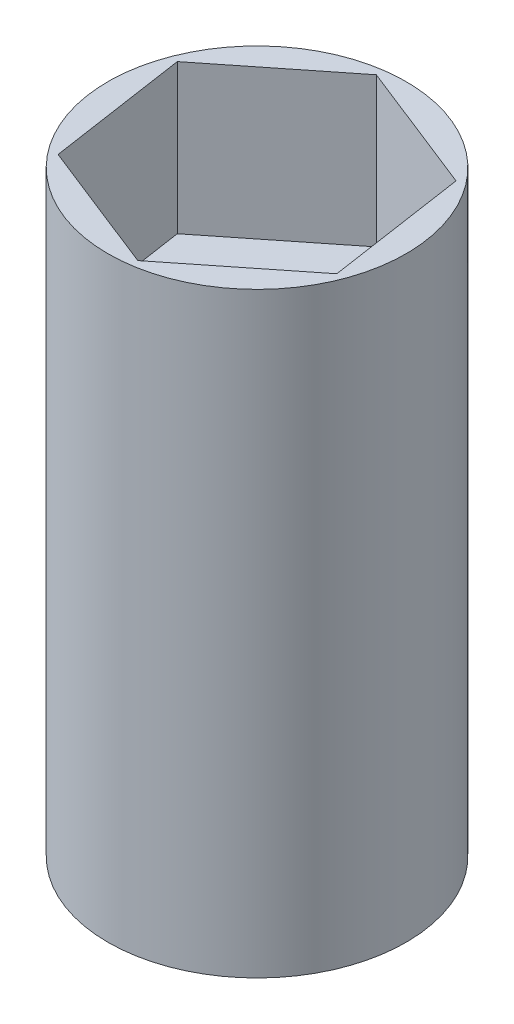
SolidWorks part; units mm, degrees
material "Alloy Steel"
ref_plane "Front Plane" through (0, 0, 0) normal (0, 0, 1) x (1, 0, 0)
ref_plane "Top Plane" through (0, 0, 0) normal (0, 1, 0) x (1, 0, 0)
ref_plane "Right Plane" through (0, 0, 0) normal (1, 0, 0) x (0, 0, -1)
sketch "Sketch1" plane through (0, 0, 0) normal (0, 1, 0) x (1, 0, 0)
  circle A0 centre (0, 0) radius 2
  dimension "D1" = 4
extrude "Boss-Extrude1" add sketch "Sketch1" along normal blind 8
sketch "Sketch2" plane through (0, 8, 0) normal (0, 1, 0) x (1, 0, 0)
  line L1 (-1.4878, -1.1817) -> (0.2795, -1.8793)
  line L2 (0.2795, -1.8793) -> (1.7673, -0.6977)
  line L3 (1.7673, -0.6977) -> (1.4878, 1.1817)
  line L4 (1.4878, 1.1817) -> (-0.2795, 1.8793)
  line L5 (-0.2795, 1.8793) -> (-1.7673, 0.6977)
  line L6 (-1.7673, 0.6977) -> (-1.4878, -1.1817)
  circle A0 centre (0, 0) radius 1.6454 construction
  dimension "D1" = 1.9
extrude "Cut-Extrude4" cut sketch "Sketch2" against normal blind 2
